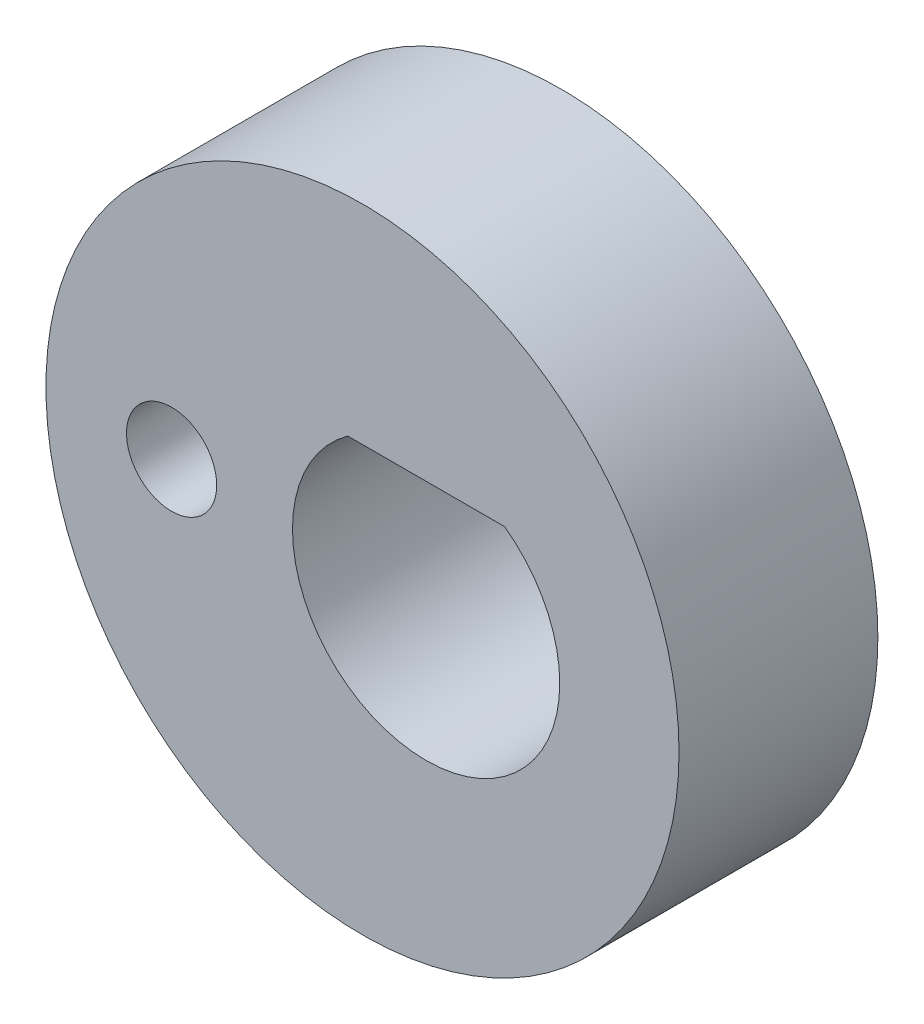
SolidWorks part; units mm, degrees
ref_plane "Front Plane" through (0, 0, 0) normal (0, 0, 1) x (1, 0, 0)
ref_plane "Top Plane" through (0, 0, 0) normal (0, 1, 0) x (1, 0, 0)
ref_plane "Right Plane" through (0, 0, 0) normal (1, 0, 0) x (0, 0, -1)
sketch "Sketch1" plane through (0, 0, 0) normal (0, 0, 1) x (1, 0, 0)
  line L0 (-1.27, 0) -> (-1.27, 2) construction
  line L5 (0, 0) -> (-1.27, 0) construction
  line L6 (0, 0) -> (0, 2.032) construction
  line L7 (-1.524, 2.032) -> (1.524, 2.032) construction
  line L8 (-1.5658, 2.159) -> (1.5658, 2.159)
  circle A0 centre (-1.27, 0) radius 6.3182
  arc A3 (-1.524, 2.032) -> (1.524, 2.032) centre (0, 0) ccw construction
  arc A4 (-1.5658, 2.159) -> (1.5658, 2.159) centre (0, 0) ccw
  point P8 (0, 2.032)
  dimension "D1" = 12.6365
  dimension "D2" = 2
  dimension "D3" = 5.08
  dimension "D4" = 2.032
  dimension "D5" = 1.27
  dimension "D6" = 0.127
extrude "Boss-Extrude1" add sketch "Sketch1" along normal blind 3.9688
sketch "Sketch8" plane through (0, 0, 3.9688) normal (0, 0, 1) x (1, 0, 0)
  line L0 (0, 0) -> (-5.08, 0) construction
  circle A0 centre (-5.08, 0) radius 0.9
  dimension "D2" = 1.8
  dimension "D1" = 5.08
extrude "Cut-Extrude2" cut sketch "Sketch8" against normal through all
